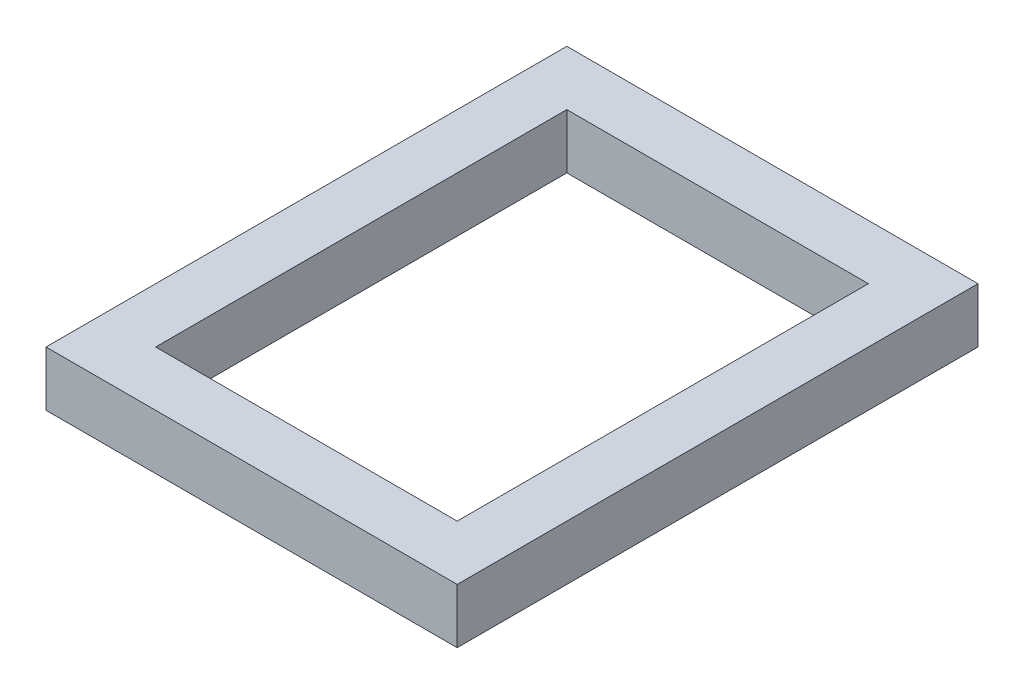
SolidWorks part; units mm, degrees
ref_plane "Front Plane" through (0, 0, 0) normal (0, 0, 1) x (1, 0, 0)
ref_plane "Top Plane" through (0, 0, 0) normal (0, 1, 0) x (1, 0, 0)
ref_plane "Right Plane" through (0, 0, 0) normal (1, 0, 0) x (0, 0, -1)
sketch "Sketch1" plane through (0, 0, 0) normal (0, 1, 0) x (1, 0, 0)
  line L1 (-47.625, -60.325) -> (47.625, -60.325)
  line L2 (-47.625, -60.325) -> (-47.625, 60.325)
  line L3 (-47.625, 60.325) -> (47.625, 60.325)
  line L4 (47.625, -60.325) -> (47.625, 60.325)
  line L5 (-47.625, -60.325) -> (47.625, 60.325) construction
  line L6 (-47.625, 60.325) -> (47.625, -60.325) construction
  line L7 (-34.925, -47.625) -> (34.925, -47.625)
  line L8 (-34.925, -47.625) -> (-34.925, 47.625)
  line L9 (-34.925, 47.625) -> (34.925, 47.625)
  line L10 (34.925, -47.625) -> (34.925, 47.625)
  line L11 (-34.925, -47.625) -> (34.925, 47.625) construction
  line L12 (-34.925, 47.625) -> (34.925, -47.625) construction
  point P0 (0, 0)
  point P5 (0, 0)
  dimension "D3" = 12.7
  dimension "D1" = 95.25
  dimension "D2" = 120.65
  dimension "D4" = 12.7
extrude "Boss-Extrude1" add sketch "Sketch1" along normal blind 12.7
